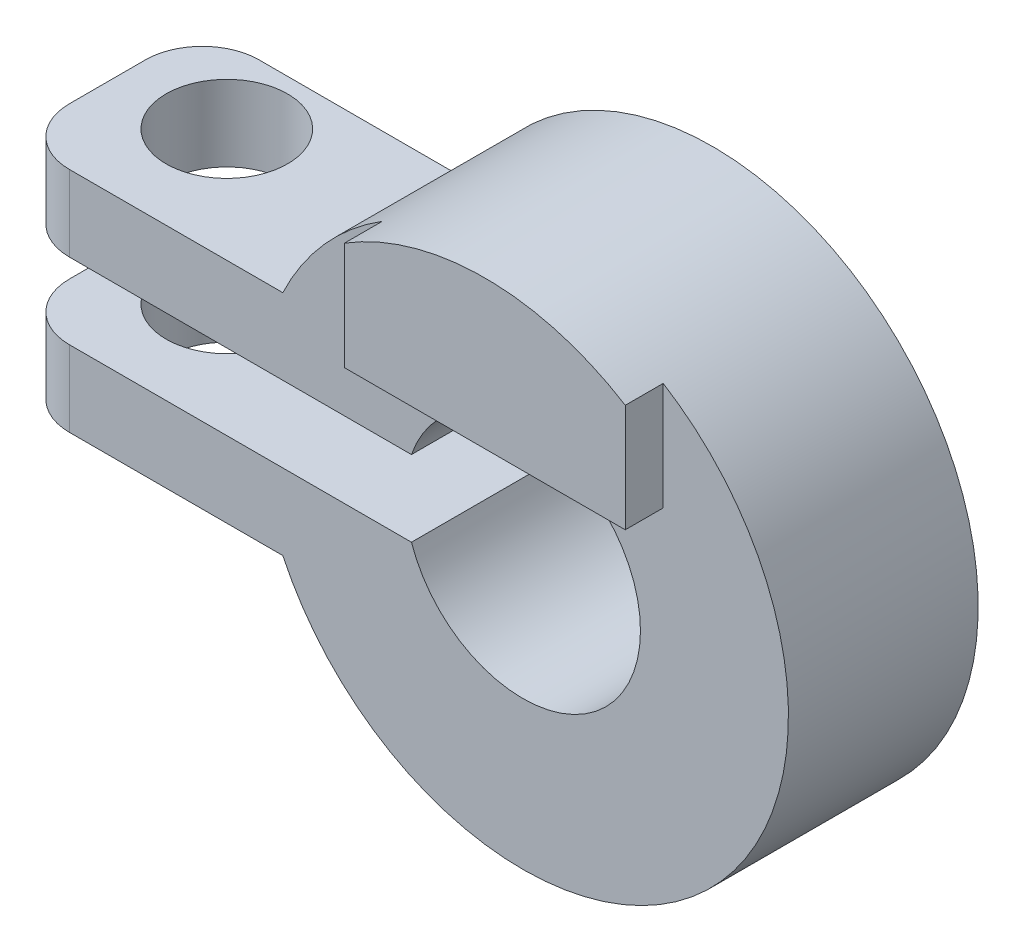
SolidWorks part; units mm, degrees
ref_plane "前视基准面" through (0, 0, 0) normal (0, 0, 1) x (1, 0, 0)
ref_plane "上视基准面" through (0, 0, 0) normal (0, 1, 0) x (1, 0, 0)
ref_plane "右视基准面" through (0, 0, 0) normal (1, 0, 0) x (0, 0, -1)
sketch "草图1" plane through (0, 0, 0) normal (0, 0, 1) x (1, 0, 0)
  circle A1 centre (0, 0) radius 14
  circle A3 centre (-7.0711, 7.0711) radius 1.5
  circle A4 centre (7.0711, 7.0711) radius 1.5
  circle A5 centre (-7.0711, -7.0711) radius 1.5
  circle A6 centre (7.0711, -7.0711) radius 1.5
extrude "凸台-拉伸1" add sketch "草图1" along normal blind 2
sketch "草图2" plane through (0, 0, 0) normal (0, 0, -1) x (-1, 0, 0)
  line L9 (-2.6885, -3.1) -> (2.6885, -3.1)
  line L10 (-2.6833, 3.1) -> (2.6833, 3.1)
  line L14 (-2.6833, -3.1) -> (2.6833, -3.1)
  arc A1 (-2.6833, 3.1) -> (-2.6833, -3.1) centre (0, 0) ccw
  arc A2 (2.6833, 3.1) -> (2.6833, -3.1) centre (0, 0) cw
  point P2 (0, 3.1)
  point P4 (0, -3.1)
extrude "切除-拉伸1" cut sketch "草图2" against normal through all contours A2 L10 A1 L9
sketch "草图3" plane through (0, 0, 0) normal (0, 0, -1) x (-1, 0, 0)
  line L0 (0, 3.1) -> (3.7, 3.1)
  line L1 (-2.6833, 3.1) -> (2.6833, 3.1) construction
  line L2 (3.7, 3.1) -> (3.7, 7.1)
  line L3 (0, 3.1) -> (-3.7, 3.1)
  line L4 (-3.7, 3.1) -> (-3.7, 7.1)
  line L5 (-3.7, 7.1) -> (3.7, 7.1)
extrude "凸台-拉伸4" add sketch "草图3" along normal blind 1
sketch "草图6" plane through (0, 0, -1) normal (0, 0, -1) x (-1, 0, 0)
  circle A2 centre (0, 0) radius 7
  circle A3 centre (0, 0) radius 3.1
extrude "凸台-拉伸5" add sketch "草图6" along normal blind 5
sketch "草图7" plane through (0, 0, -6) normal (0, 0, -1) x (-1, 0, 0)
  line L0 (-2.5, 3.1) -> (-2.5, 6.5383)
  line L2 (-2.5, 3.1) -> (2.5, 3.1)
  line L3 (2.5, 6.5383) -> (2.5, 3.1)
  arc A2 (-2.5, 6.5383) -> (2.5, 6.5383) centre (0, 0) cw
  point P17 (0, 3.1)
extrude "凸台-拉伸6" add sketch "草图7" along normal blind 1
sketch "草图8" plane through (0, 0, -6) normal (0, 0, -1) x (-1, 0, 0)
  line L2 (5.4474, 3) -> (5.4474, 1)
  line L5 (5.4474, 1) -> (13.4474, 1)
  line L6 (13.4474, 1) -> (13.4474, 3)
  line L7 (13.4474, 3) -> (5.4474, 3)
  line L10 (5.4474, -3) -> (13.4474, -3)
  line L11 (13.4474, -3) -> (13.4474, -1)
  line L12 (13.4474, -1) -> (5.4474, -1)
  line L14 (5.4474, -1) -> (5.4474, -3)
extrude "凸台-拉伸7" add sketch "草图8" against normal blind 5
sketch "草图9" plane through (0, 3, 0) normal (0, 1, 0) x (1, 0, 0)
  circle A0 centre (-10.8, 4) radius 1.6
extrude "切除-拉伸3" cut sketch "草图9" against normal through all contours A0
sketch "草图10" plane through (0, 0, -7) normal (0, 0, -1) x (-1, 0, 0)
  line L9 (-2.5, 6.5383) -> (-2.5, 3.1)
  line L10 (2.5, 6.5383) -> (2.5, 3.1)
  arc A2 (-2.5, 3.1) -> (2.5, 3.1) centre (0, 0) ccw
  arc A3 (-2.5, 6.5383) -> (2.5, 6.5383) centre (0, 0) cw
extrude "凸台-拉伸8" add sketch "草图10" along normal blind 2
sketch "草图11" plane through (0, 0, -6) normal (0, 0, -1) x (-1, 0, 0)
  line L0 (13.4474, 1) -> (1.4059, 1)
  line L1 (13.4474, -1) -> (1.4059, -1)
  line L2 (1.4059, -1) -> (1.4059, 1)
  line L3 (13.4474, 1) -> (13.4474, -1)
extrude "切除-拉伸4" cut sketch "草图11" against normal blind 5
sketch "草图12" plane through (0, 0, 2) normal (0, 0, 1) x (1, 0, 0)
  circle A0 centre (0, 0) radius 20
  circle A1 centre (0, 0) radius 3.1
extrude "凸台-拉伸9" add sketch "草图12" against normal blind 2
sketch "草图13" plane through (0, 0, 2) normal (0, 0, 1) x (1, 0, 0)
  line L6 (-10.253, -10.253) -> (10.253, 10.253) construction
  line L7 (-10.253, 10.253) -> (10.253, -10.253) construction
  circle A0 centre (10.253, 10.253) radius 2.3
  circle A1 centre (-10.253, 10.253) radius 2.3
  circle A2 centre (-10.253, -10.253) radius 2.3
  circle A3 centre (10.253, -10.253) radius 2.3
extrude "切除-拉伸5" cut sketch "草图13" against normal blind 2
sketch "草图14" plane through (0, 0, -1) normal (0, 0, -1) x (-1, 0, 0)
  line L0 (-4.5909, 5.2843) -> (-4.5909, 9.7386)
  line L1 (-4.5909, 9.7386) -> (4.7248, 9.7386)
  line L2 (4.7248, 9.7386) -> (4.7248, 5.1649)
  arc A0 (-4.5909, 5.2843) -> (4.7248, 5.1649) centre (0, 0) cw
  arc A1 (-2.5, 6.5383) -> (6.3246, -3) centre (0, 0) ccw construction
extrude "切除-拉伸6" cut sketch "草图14" against normal blind 1
fillet "圆角1" radius 3 1 edges at (0, 7, -9)
fillet "圆角2" radius 1.5 4 edges at (-13.4474, 2, -6) (-13.4474, 2, -1) (-13.4474, -2, -6) (-13.4474, -2, -1)
sketch "草图15" plane through (0, 0, 2) normal (0, 0, 1) x (1, 0, 0)
  circle A0 centre (0, 0) radius 20
extrude "切除-拉伸7" cut sketch "草图15" against normal blind 2
sketch "草图16" plane through (0, 0, -6) normal (0, 0, -1) x (-1, 0, 0)
  circle A0 centre (0, 0) radius 7
extrude "切除-拉伸8" cut sketch "草图16" along normal blind 5
